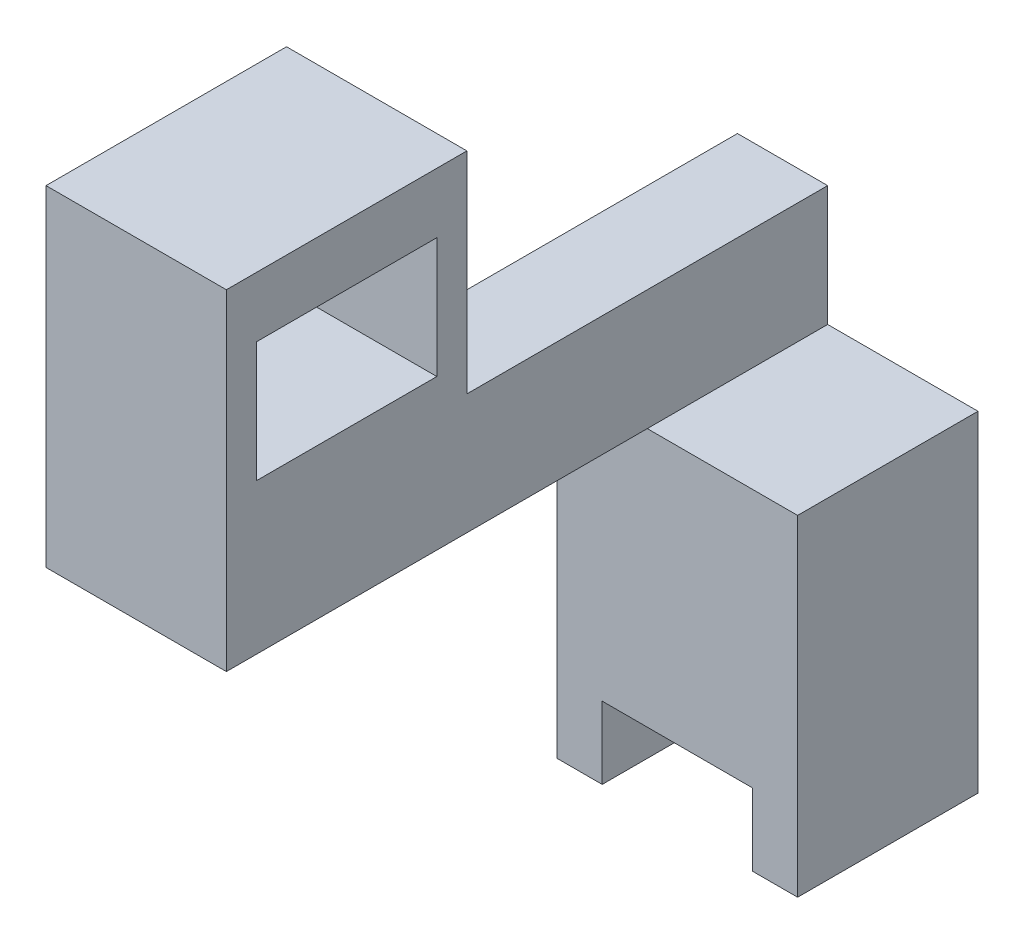
SolidWorks part; units mm, degrees
ref_plane "Спереди" through (0, 0, 0) normal (0, 0, 1) x (1, 0, 0)
ref_plane "Сверху" through (0, 0, 0) normal (0, 1, 0) x (1, 0, 0)
ref_plane "Справа" through (0, 0, 0) normal (1, 0, 0) x (0, 0, -1)
sketch "Эскиз1" plane through (0, 0, 0) normal (0, 0, 1) x (1, 0, 0)
  line L1 (-15, -27.5) -> (15, -27.5)
  line L2 (-15, -27.5) -> (-15, 27.5)
  line L3 (-15, 27.5) -> (15, 27.5)
  line L4 (15, -27.5) -> (15, 27.5)
  line L5 (-15, -27.5) -> (15, 27.5) construction
  line L6 (-15, 27.5) -> (15, -27.5) construction
  point P0 (0, 0)
  dimension "D1" = 30
  dimension "D2" = 55
extrude "Бобышка-Вытянуть1" add sketch "Эскиз1" along normal blind 40
sketch "Эскиз4" plane through (15, 0, 0) normal (1, 0, 0) x (0, 0, -1)
  line L0 (-20, 27.5) -> (-20, -27.5) construction
  line L1 (-40, 27.5) -> (0, 27.5) construction
  line L2 (-40, -27.5) -> (0, -27.5) construction
  line L4 (-35, -2.5) -> (-5, -2.5)
  line L5 (-35, -2.5) -> (-35, 17.5)
  line L6 (-35, 17.5) -> (-5, 17.5)
  line L7 (-5, -2.5) -> (-5, 17.5)
  line L8 (-35, -2.5) -> (-5, 17.5) construction
  line L9 (-35, 17.5) -> (-5, -2.5) construction
  point P6 (-20, 7.5)
  dimension "D1" = 30
  dimension "D2" = 20
  dimension "D3" = 10
extrude "Вырез-Вытянуть1" cut sketch "Эскиз4" against normal through all
sketch "Эскиз5" plane through (0, 0, 0) normal (0, 0, -1) x (-1, 0, 0)
  line L1 (-15, -27.5) -> (0, -27.5)
  line L2 (-15, -27.5) -> (-15, -7.5)
  line L3 (-15, -7.5) -> (0, -7.5)
  line L4 (0, -27.5) -> (0, -7.5)
  dimension "D1" = 15
  dimension "D2" = 20
extrude "Бобышка-Вытянуть3" add sketch "Эскиз5" along normal blind 60
sketch "Эскиз6" plane through (0, -27.5, 0) normal (0, -1, 0) x (1, 0, 0)
  line L0 (-15, 40) -> (-15, 0) construction
  line L1 (0, -60) -> (40, -60)
  line L2 (0, -60) -> (0, -30)
  line L3 (0, -30) -> (40, -30)
  line L4 (40, -60) -> (40, -30)
  line L5 (-15, 40) -> (15, 40) construction
extrude "Бобышка-Вытянуть4" add sketch "Эскиз6" along normal blind 55
sketch "Эскиз7" plane through (0, 0, -30) normal (0, 0, 1) x (1, 0, 0)
  line L0 (40, -82.5) -> (0, -82.5) construction
  line L1 (7.5, -70.5) -> (32.5, -70.5)
  line L2 (7.5, -70.5) -> (7.5, -82.5)
  line L3 (7.5, -82.5) -> (32.5, -82.5)
  line L4 (32.5, -70.5) -> (32.5, -82.5)
  line L5 (7.5, -70.5) -> (32.5, -82.5) construction
  line L6 (7.5, -82.5) -> (32.5, -70.5) construction
  line L7 (20, -82.5) -> (20, -27.5) construction
  line L8 (40, -27.5) -> (15, -27.5) construction
  point P0 (20, -76.5)
  dimension "D1" = 12
  dimension "D2" = 25
extrude "Вырез-Вытянуть2" cut sketch "Эскиз7" against normal through all
